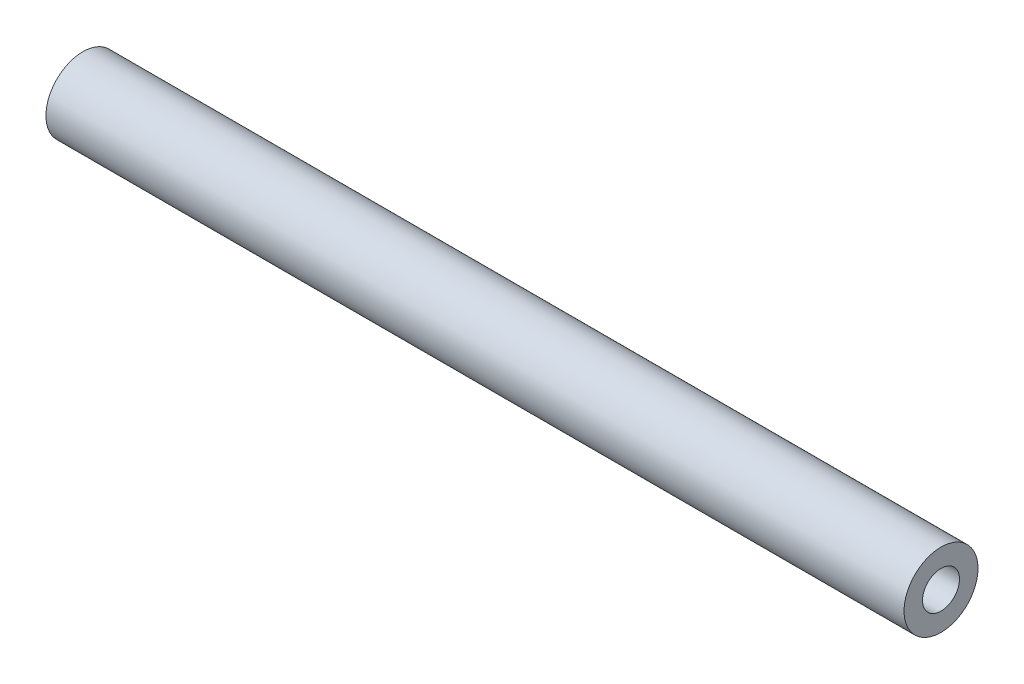
SolidWorks part; units mm, degrees
ref_plane "Front Plane" through (0, 0, 0) normal (0, 0, 1) x (1, 0, 0)
ref_plane "Top Plane" through (0, 0, 0) normal (0, 1, 0) x (1, 0, 0)
ref_plane "Right Plane" through (0, 0, 0) normal (1, 0, 0) x (0, 0, -1)
sketch "Sketch1" plane through (0, 0, 0) normal (1, 0, 0) x (0, 0, -1)
  circle A0 centre (0, 0) radius 5
  dimension "D1" = 10
extrude "Boss-Extrude1" add sketch "Sketch1" against normal blind 116
sketch "Sketch2" plane through (0, 0, 0) normal (1, 0, 0) x (0, 0, -1)
  circle A0 centre (0, 0) radius 2.5
  dimension "D1" = 5
extrude "Cut-Extrude1" cut sketch "Sketch2" against normal blind 26
